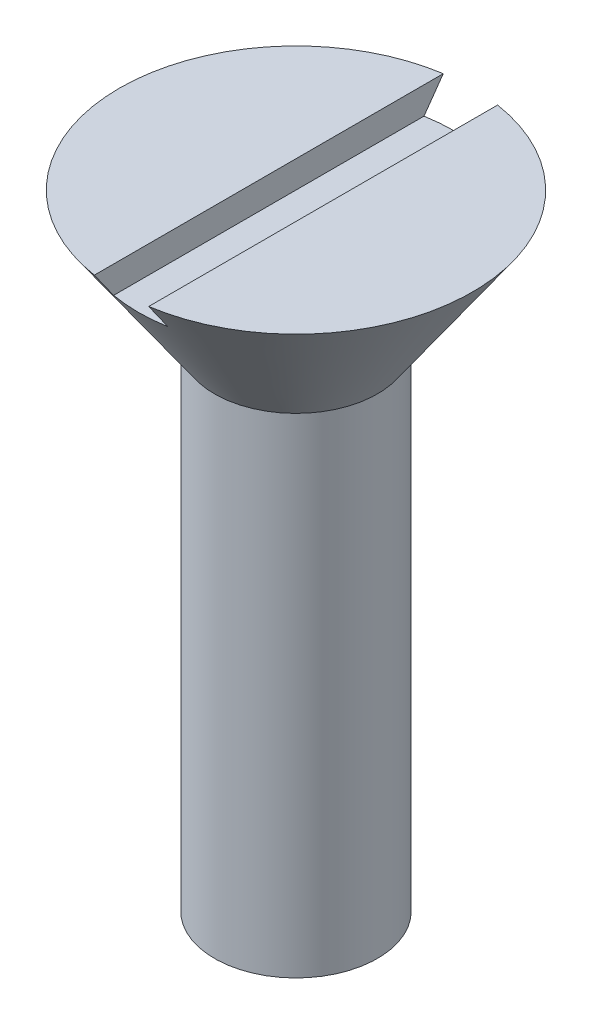
SolidWorks part; units mm, degrees
ref_plane "Front Plane" through (0, 0, 0) normal (0, 0, 1) x (1, 0, 0)
ref_plane "Top Plane" through (0, 0, 0) normal (0, 1, 0) x (1, 0, 0)
ref_plane "Right Plane" through (0, 0, 0) normal (1, 0, 0) x (0, 0, -1)
sketch "Sketch2" plane through (0, 0, 0) normal (0, 0, 1) x (1, 0, 0)
  line L0 (0, 16.4123) -> (0, -16.4123) construction
  line L1 (6.5, 6.5877) -> (0, 6.5877)
  line L2 (0, 6.5877) -> (0, 16.4123) construction
  line L4 (3, -16.4123) -> (3, 1.5877)
  line L5 (0, 6.5877) -> (0, -16.4123)
  line L6 (6.5, 6.5877) -> (3, 1.5877)
  line L7 (0, -16.4123) -> (0, -18.1444)
  line L8 (0, -18.1444) -> (3, -16.4123)
  point P4 (0, 0)
  dimension "D1" = 5
  dimension "D2" = 18
  dimension "D3" = 13
  dimension "D4" = 6
  dimension "D5" = 60
revolve "Revolve1" add sketch "Sketch2" angle 360 about L5
sketch "Sketch4" plane through (0, 6.5877, 0) normal (0, 1, 0) x (1, 0, 0)
  line L0 (0, 6.5) -> (0, -6.5) construction
  line L3 (-1, 6.4226) -> (-1, -6.4226)
  line L4 (1, 6.4226) -> (1, -6.4226)
  line L7 (-1, -6.4226) -> (-1, -6.6229)
  line L8 (-1, -6.6229) -> (1, -6.6229)
  line L9 (1, -6.6229) -> (1, -6.4226)
  line L10 (-1, 6.4226) -> (-1, 6.9862)
  line L11 (-1, 6.9862) -> (1, 6.9862)
  line L12 (1, 6.9862) -> (1, 6.4226)
  circle A0 centre (0, 0) radius 6.5 construction
  point P7 (0, 0)
  point P14 (-1, 0)
  point P17 (1, 0)
  dimension "D1" = 13
extrude "Cut-Extrude2" cut sketch "Sketch4" against normal blind 1
